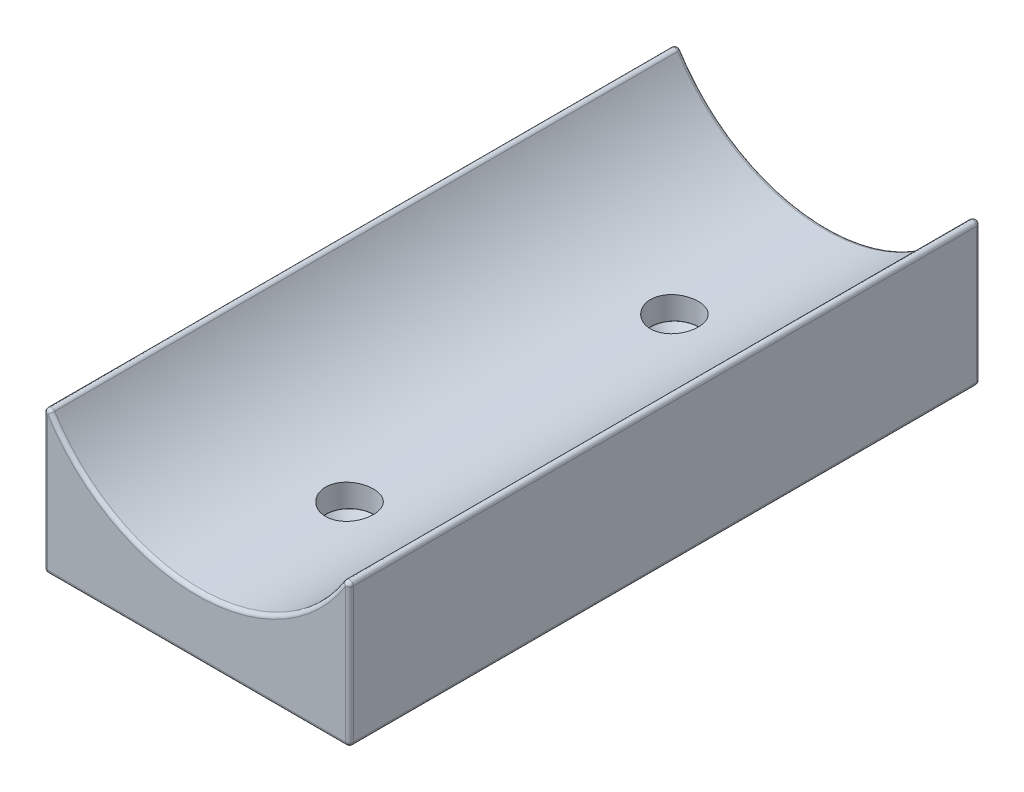
SolidWorks part; units mm, degrees
ref_plane "Front Plane" through (0, 0, 0) normal (0, 0, 1) x (1, 0, 0)
ref_plane "Top Plane" through (0, 0, 0) normal (0, 1, 0) x (1, 0, 0)
ref_plane "Right Plane" through (0, 0, 0) normal (1, 0, 0) x (0, 0, -1)
sketch "Sketch2" plane through (0, 0, 0) normal (0, 0, 1) x (1, 0, 0)
  line L1 (0, 0) -> (40.64, 0)
  line L2 (0, 0) -> (0, 20.3883)
  line L4 (40.64, 0) -> (40.64, 20.3883)
  arc A0 (0, 20.3883) -> (40.64, 20.3883) centre (20.32, 30.861) ccw
  dimension "D3" = 45.72
  dimension "D1" = 40.64
  dimension "D2" = 30.861
  dimension "D4" = 20.32
extrude "Boss-Extrude1" add sketch "Sketch2" along normal blind 83.82
fillet "Fillet1" radius 0.508 2 edges at (40.64, 20.3883, 41.91) (0, 20.3883, 41.91)
sketch "Sketch5" plane through (0, 0, 0) normal (0, 1, 0) x (1, 0, 0)
  line L0 (0, -83.82) -> (0, 0) construction
  line L1 (39.7013, 0) -> (0.9387, 0) construction
  line L2 (0.9387, -83.82) -> (39.7013, -83.82) construction
  circle A0 centre (20.32, -20.32) radius 3.175
  circle A1 centre (20.32, -63.5) radius 3.175
  dimension "D1" = 6.35
  dimension "D2" = 6.35
  dimension "D3" = 20.32
  dimension "D4" = 20.32
  dimension "D5" = 20.32
  dimension "D6" = 20.32
extrude "Cut-Extrude1" cut sketch "Sketch5" along normal through all from offset 5.08
hole_wizard "CSK for M3 Countersunk Flat Head Screw1" positions "Sketch8" profile "Sketch7" countersink size "M3" standard "ISO"
sketch "Sketch8" plane through (0, 5.08, 0) normal (0, 1, 0) x (1, 0, 0)
  point P0 (20.32, -20.32)
  point P3 (20.32, -63.5)
sketch "Sketch7" plane through (20.32, 5.08, 20.32) normal (1, 0, 0) x (0, 0, 1)
  line L0 (0, 0) -> (0, 420.4355)
  line L1 (0, 420.4355) -> (1.8, 419.354)
  line L2 (1.8, 419.354) -> (1.8, 1.35)
  line L3 (1.8, 1.35) -> (3.15, 0)
  line L5 (3.15, 0) -> (0, 0)
  line L6 (-1.8, 1.35) -> (-3.15, 0) construction
  line L10 (0, 420.4355) -> (-1.8, 419.354) construction
  line L11 (0, -6.35) -> (0, 107.95) construction
  dimension "Hole Dia." = 3.6
  dimension "Hole Depth" = 419.354
  dimension "Near C'Sink Dia." = 6.3
  dimension "Near C'Sink Angle" = 90
  dimension "Drill Angle" = 118
fillet "Fillet2" radius 0.508 14 edges at (40.64, 9.2348, 0) (40.2721, 18.9578, 0) (20.32, 8.001, 0) (0.3679, 18.9578, 0) (40.64, 9.2348, 83.82) (40.2721, 18.9578, 83.82) (0, 9.2348, 83.82) (0.3679, 18.9578, 83.82) (20.32, 0, 0) (0, 9.2348, 0) (0, 0, 41.91) (20.32, 0, 83.82) (40.64, 0, 41.91) (20.32, 8.001, 83.82)
